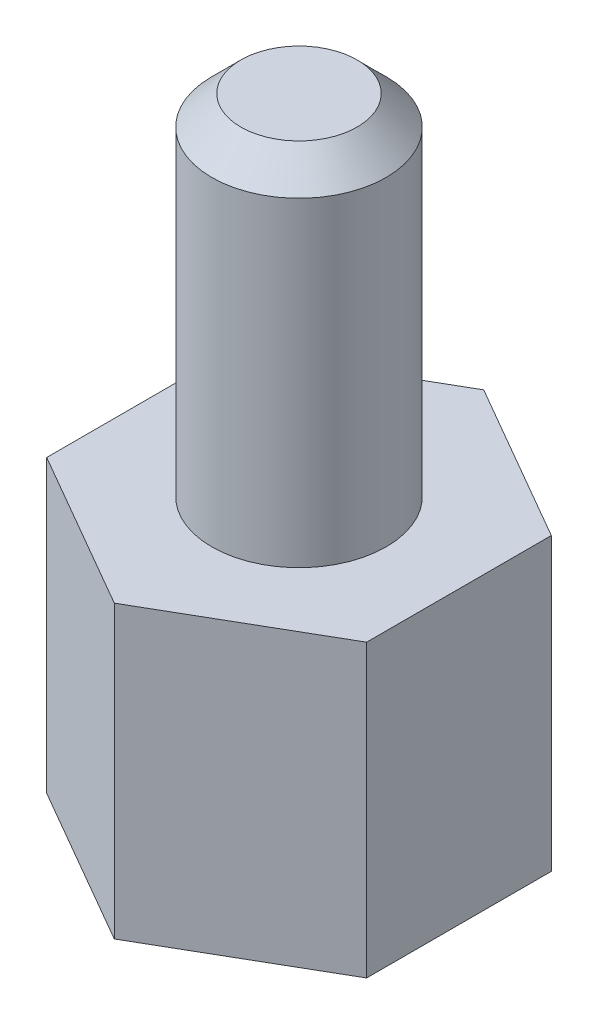
SolidWorks part; units mm, degrees
material "AISI 1010 Сталь, горяченакатанная полоса"
ref_plane "Спереди" through (0, 0, 0) normal (0, 0, 1) x (1, 0, 0)
ref_plane "Сверху" through (0, 0, 0) normal (0, 1, 0) x (1, 0, 0)
ref_plane "Справа" through (0, 0, 0) normal (1, 0, 0) x (0, 0, -1)
sketch "Эскиз1" plane through (0, 0, 0) normal (0, 1, 0) x (1, 0, 0)
  line L1 (0, 3.1754) -> (-2.75, 1.5877)
  line L2 (-2.75, 1.5877) -> (-2.75, -1.5877)
  line L3 (-2.75, -1.5877) -> (0, -3.1754)
  line L4 (0, -3.1754) -> (2.75, -1.5877)
  line L5 (2.75, -1.5877) -> (2.75, 1.5877)
  line L6 (2.75, 1.5877) -> (0, 3.1754)
  circle A0 centre (0, 0) radius 2.75 construction
  dimension "D1" = 5.5
extrude "Бобышка-Вытянуть1" add sketch "Эскиз1" along normal blind 5
sketch "Эскиз2" plane through (0, 5, 0) normal (0, 1, 0) x (1, 0, 0)
  circle A0 centre (0, 0) radius 1.5
extrude "Бобышка-Вытянуть2" add sketch "Эскиз2" along normal blind 6
chamfer "Фаска1" distance 0.5 angle 45 1 edges at (0, 11, 1.5)
hole_wizard "Отверстие обработанное метчиком M31" positions "Эскиз4" profile "Эскиз3" tap size "M3" standard "Iso"
sketch "Эскиз4" plane through (0, 0, 0) normal (0, -1, 0) x (-1, 0, 0)
  point P0 (0, 0)
sketch "Эскиз3" plane through (0, 0, 0) normal (1, 0, 0) x (0, 0, -1)
  line L0 (0, 0) -> (0, 9.2511)
  line L1 (0, 9.2511) -> (1.25, 8.5)
  line L2 (1.25, 8.5) -> (1.25, 0)
  line L5 (1.25, 0) -> (0, 0)
  line L10 (0, 9.2511) -> (-1.25, 8.5) construction
  line L11 (0, -6.35) -> (0, 107.95) construction
  dimension "Диаметр сверла" = 2.5
  dimension "Глубина сверла" = 8.5
  dimension "Угол заточки сверла" = 118
cosmetic thread "Отверстие резьбы1" parameters "D1"=6, "D2"=3
